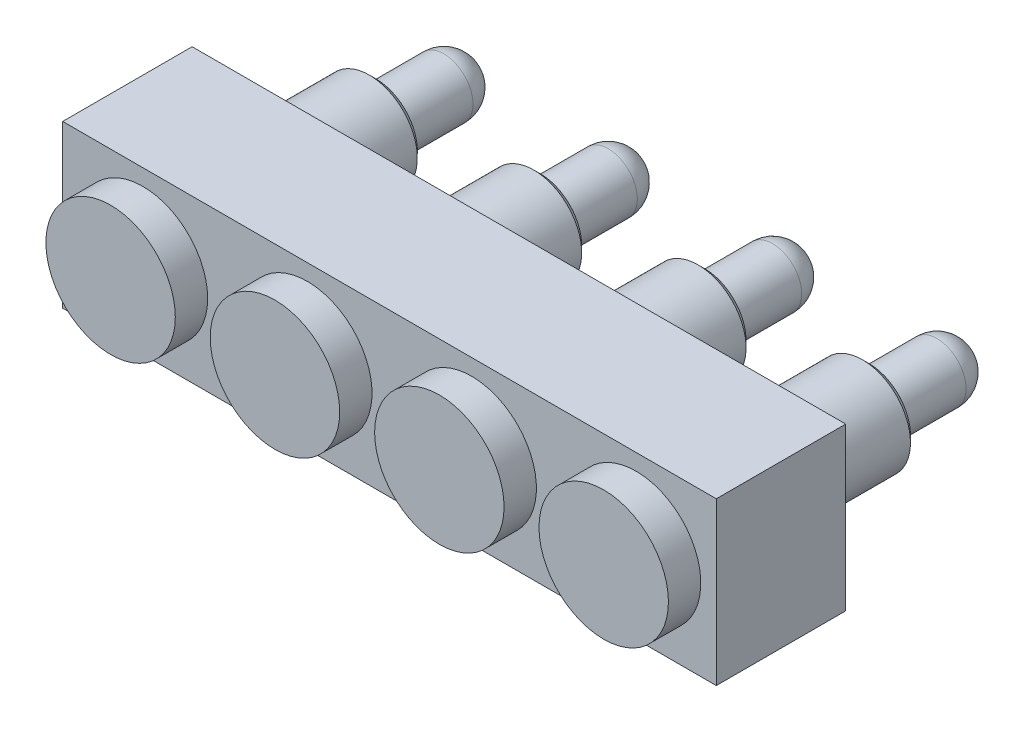
SolidWorks part; units mm, degrees
ref_plane "前视基准面" through (0, 0, 0) normal (0, 0, 1) x (1, 0, 0)
ref_plane "上视基准面" through (0, 0, 0) normal (0, 1, 0) x (1, 0, 0)
ref_plane "右视基准面" through (0, 0, 0) normal (1, 0, 0) x (0, 0, -1)
sketch "草图1" plane through (0, 0, 0) normal (0, 0, 1) x (1, 0, 0)
  line L0 (0.0041, 1.2525) -> (10.1041, 1.2525) construction
  line L1 (0.0041, 0.0025) -> (10.1041, 0.0025)
  line L2 (0.0041, 0.0025) -> (0.0041, 2.5025)
  line L3 (0.0041, 2.5025) -> (10.1041, 2.5025)
  line L4 (10.1041, 0.0025) -> (10.1041, 2.5025)
  line L5 (5.0541, 2.5025) -> (5.0541, 0.0025) construction
  circle A0 centre (3.7841, 1.2525) radius 0.74
  circle A4 centre (1.2441, 1.2525) radius 0.74
  circle A5 centre (8.8641, 1.2525) radius 0.74
  circle A6 centre (6.3241, 1.2525) radius 0.74
  dimension "D3" = 1.48
  dimension "D1" = 10.1
  dimension "D2" = 2.5
  dimension "D4" = 1.27
  dimension "D5" = 2
extrude "凸台-拉伸1" add sketch "草图1" along normal blind 2
ref_plane "基准面1" through (0, 0, 2) normal (0, 0, 1) x (1, 0, 0)
sketch "草图2" plane through (0, 0, 2) normal (0, 0, 1) x (1, 0, 0)
  circle A0 centre (1.2441, 1.2525) radius 1
  circle A1 centre (3.7841, 1.2525) radius 1
  circle A2 centre (6.3241, 1.2525) radius 1
  circle A3 centre (8.8641, 1.2525) radius 1
  dimension "D1" = 2
  dimension "D2" = 4
extrude "凸台-拉伸2" add sketch "草图2" along normal blind 0.5
ref_plane "基准面2" through (0, 0, 0) normal (0, 0, -1) x (-1, 0, 0)
sketch "草图3" plane through (0, 0, 0) normal (0, 0, -1) x (-1, 0, 0)
  circle A0 centre (-1.2441, 1.2525) radius 0.74
  circle A1 centre (-3.7841, 1.2525) radius 0.74
  circle A2 centre (-6.3241, 1.2525) radius 0.74
  circle A3 centre (-8.8641, 1.2525) radius 0.74
  dimension "D1" = 1.48
  dimension "D2" = 4
extrude "凸台-拉伸3" add sketch "草图3" along normal blind 1.6 separate body
sketch "草图4" plane through (0, 0, 0) normal (0, 0, -1) x (-1, 0, 0)
  circle A0 centre (-8.8641, 1.2525) radius 0.45
  circle A1 centre (-6.3241, 1.2525) radius 0.45
  circle A2 centre (-3.7841, 1.2525) radius 0.45
  circle A3 centre (-1.2441, 1.2525) radius 0.45
  dimension "D1" = 4
extrude "凸台-拉伸4" add sketch "草图4" along normal blind 3.1
fillet "圆角1" radius 0.45 1 edges at (8.4141, 1.2525, -3.1)
fillet "圆角2" radius 0.45 1 edges at (5.8741, 1.2525, -3.1)
fillet "圆角3" radius 0.45 1 edges at (3.3341, 1.2525, -3.1)
fillet "圆角4" radius 0.45 1 edges at (0.7941, 1.2525, -3.1)
chamfer "倒角1" distance 0.1 angle 45 1 edges at (8.1241, 1.2525, -1.6)
chamfer "倒角2" distance 0.1 angle 45 1 edges at (5.5841, 1.2525, -1.6)
chamfer "倒角3" distance 0.1 angle 45 1 edges at (3.0441, 1.2525, -1.6)
chamfer "倒角4" distance 0.1 angle 45 1 edges at (0.5041, 1.2525, -1.6)
